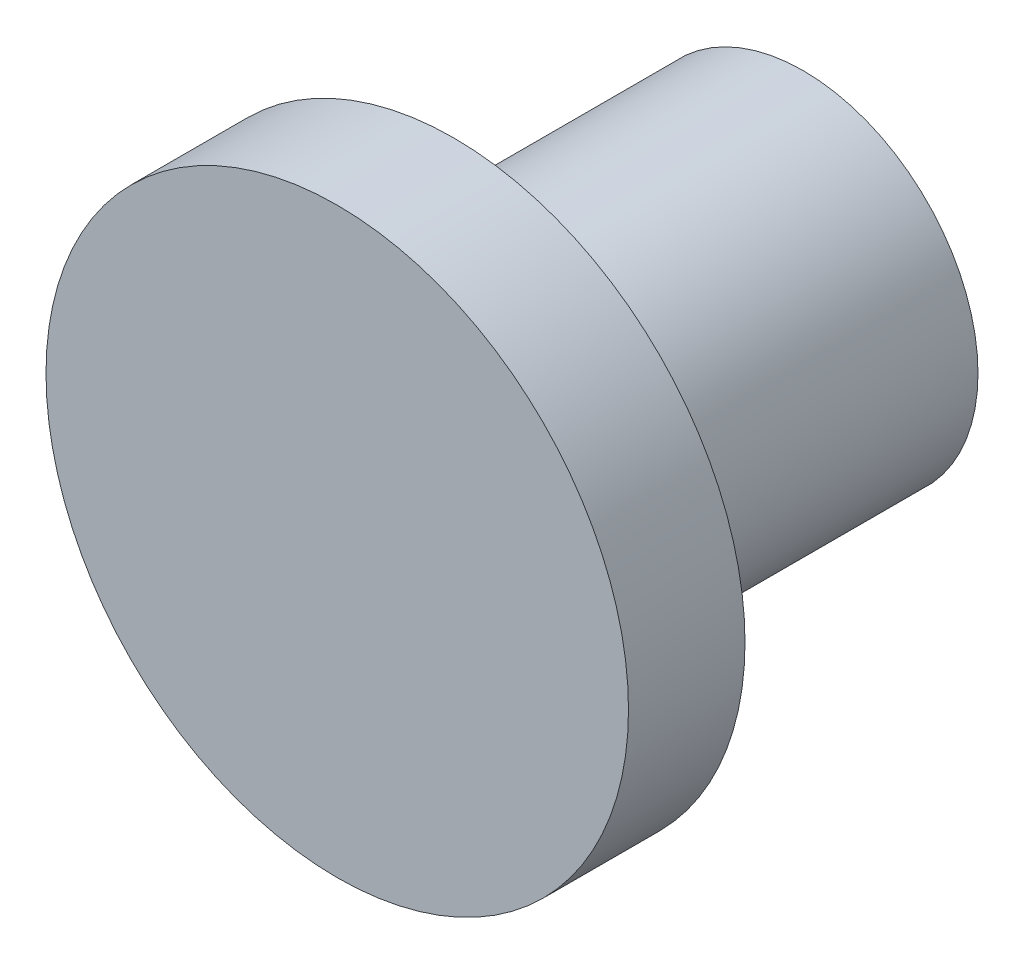
SolidWorks part; units mm, degrees
ref_plane "Front Plane" through (0, 0, 0) normal (0, 0, 1) x (1, 0, 0)
ref_plane "Top Plane" through (0, 0, 0) normal (0, 1, 0) x (1, 0, 0)
ref_plane "Right Plane" through (0, 0, 0) normal (1, 0, 0) x (0, 0, -1)
sketch "Sketch1" plane through (0, 0, 0) normal (0, 0, 1) x (1, 0, 0)
  circle A0 centre (0, 0) radius 1.5
  dimension "D1" = 3
extrude "Boss-Extrude1" add sketch "Sketch1" along normal blind 3
sketch "Sketch2" plane through (0, 0, 3) normal (0, 0, 1) x (1, 0, 0)
  circle A0 centre (0, 0) radius 2.5
  dimension "D1" = 5
extrude "Boss-Extrude2" add sketch "Sketch2" along normal blind 1
